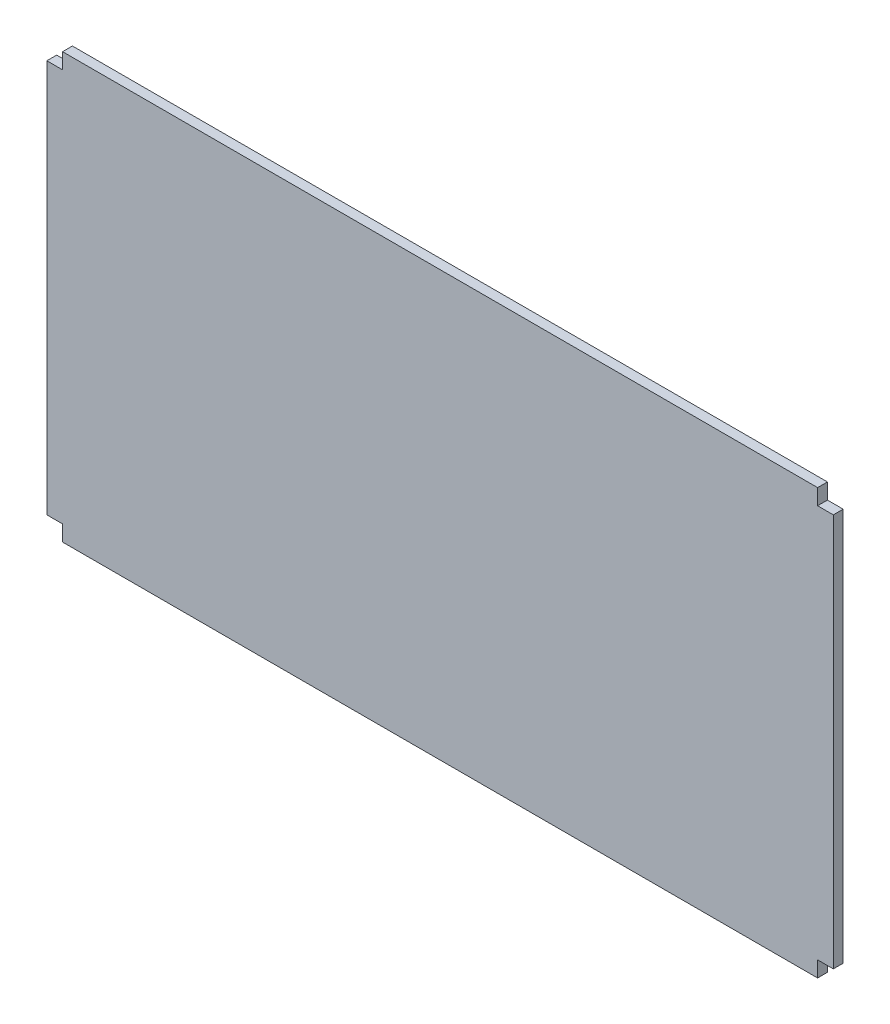
SolidWorks part; units mm, degrees
material "Custom Plastic"
ref_plane "Front Plane" through (0, 0, 0) normal (0, 0, 1) x (1, 0, 0)
ref_plane "Top Plane" through (0, 0, 0) normal (0, 1, 0) x (1, 0, 0)
ref_plane "Right Plane" through (0, 0, 0) normal (1, 0, 0) x (0, 0, -1)
sketch "Sketch1" plane through (0, 0, 0) normal (0, 0, 1) x (1, 0, 0)
  line L0 (-500, 125) -> (-480, 125)
  line L3 (-480, 145) -> (480, 145)
  line L5 (500, -375) -> (480, -375)
  line L6 (-500, -155) -> (-500, 125)
  line L7 (-480, 125) -> (-480, 145)
  line L10 (480, 145) -> (480, 125)
  line L11 (480, 125) -> (500, 125)
  line L18 (500, 125) -> (500, -375)
  line L19 (-500, -155) -> (-500, -375)
  line L20 (-480, -395) -> (480, -395)
  line L21 (480, -395) -> (480, -375)
  line L22 (-500, -375) -> (-480, -375)
  line L23 (-480, -375) -> (-480, -395)
  point P0 (0, 0)
  dimension "D1" = 20
  dimension "D2" = 20
  dimension "D7" = 20
  dimension "D8" = 20
extrude "Boss-Extrude1" add sketch "Sketch1" along normal blind 12.5
